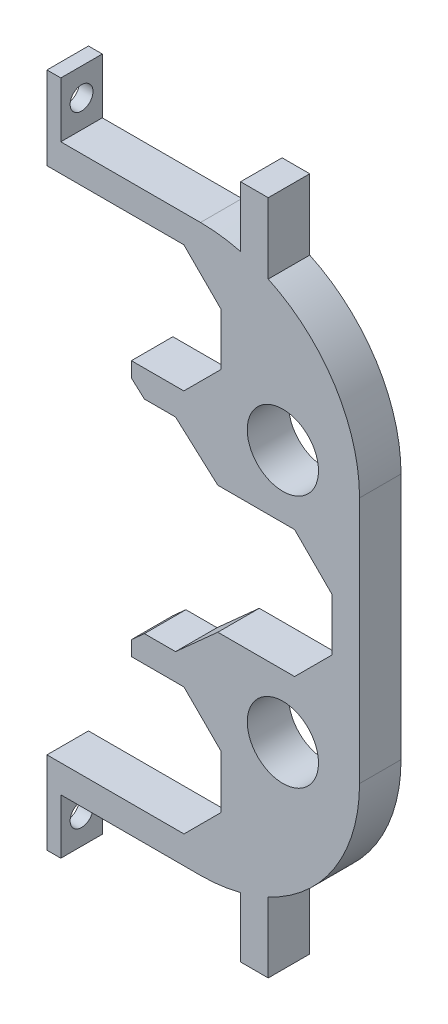
SolidWorks part; units mm, degrees
ref_plane "前视基准面" through (0, 0, 0) normal (0, 0, 1) x (1, 0, 0)
ref_plane "上视基准面" through (0, 0, 0) normal (0, 1, 0) x (1, 0, 0)
ref_plane "右视基准面" through (0, 0, 0) normal (1, 0, 0) x (0, 0, -1)
other "Configuration Table"
sketch "草图1" plane through (0, 0, 228) normal (0, 0, 1) x (1, 0, 0)
  line L0 (25.0533, -31.4628) -> (19.75, -36.7661) construction
  line L1 (19.75, -36.7661) -> (12.25, -36.7661) construction
  line L2 (12.25, -36.7661) -> (6.9467, -31.4628) construction
  line L3 (6.9467, -31.4628) -> (6.9467, -23.9628) construction
  line L4 (6.9467, -23.9628) -> (12.25, -18.6595) construction
  line L5 (12.25, -18.6595) -> (19.75, -18.6595) construction
  line L6 (19.75, -18.6595) -> (25.0533, -23.9628) construction
  line L7 (25.0533, -23.9628) -> (25.0533, -31.4628) construction
  line L8 (41.0533, -3.75) -> (35.75, -9.0533) construction
  line L9 (35.75, -9.0533) -> (28.25, -9.0533) construction
  line L10 (28.25, -9.0533) -> (22.9467, -3.75) construction
  line L11 (22.9467, -3.75) -> (22.9467, 3.75) construction
  line L12 (22.9467, 3.75) -> (28.25, 9.0533) construction
  line L13 (28.25, 9.0533) -> (35.75, 9.0533) construction
  line L14 (35.75, 9.0533) -> (41.0533, 3.75) construction
  line L15 (41.0533, 3.75) -> (41.0533, -3.75) construction
  line L16 (25.0533, 23.9628) -> (19.75, 18.6595) construction
  line L17 (19.75, 18.6595) -> (12.25, 18.6595) construction
  line L18 (12.25, 18.6595) -> (6.9467, 23.9628) construction
  line L19 (6.9467, 23.9628) -> (6.9467, 31.4628) construction
  line L20 (6.9467, 31.4628) -> (12.25, 36.7661) construction
  line L21 (12.25, 36.7661) -> (19.75, 36.7661) construction
  line L22 (19.75, 36.7661) -> (25.0533, 31.4628) construction
  line L23 (25.0533, 31.4628) -> (25.0533, 23.9628) construction
  line L24 (25.0533, -31.4628) -> (19.75, -36.7661) construction
  line L25 (19.75, -36.7661) -> (12.25, -36.7661) construction
  line L26 (12.25, -36.7661) -> (6.9467, -31.4628) construction
  line L27 (6.9467, -31.4628) -> (6.9467, -23.9628) construction
  line L28 (6.9467, -23.9628) -> (12.25, -18.6595) construction
  line L29 (12.25, -18.6595) -> (19.75, -18.6595) construction
  line L30 (19.75, -18.6595) -> (25.0533, -23.9628) construction
  line L31 (25.0533, -23.9628) -> (25.0533, -31.4628) construction
  line L32 (41.0533, -3.75) -> (35.75, -9.0533) construction
  line L33 (35.75, -9.0533) -> (28.25, -9.0533) construction
  line L34 (28.25, -9.0533) -> (22.9467, -3.75) construction
  line L35 (22.9467, -3.75) -> (22.9467, 3.75) construction
  line L36 (22.9467, 3.75) -> (28.25, 9.0533) construction
  line L37 (28.25, 9.0533) -> (35.75, 9.0533) construction
  line L38 (35.75, 9.0533) -> (41.0533, 3.75) construction
  line L39 (41.0533, 3.75) -> (41.0533, -3.75) construction
  line L40 (25.0533, 23.9628) -> (19.75, 18.6595) construction
  line L41 (19.75, 18.6595) -> (12.25, 18.6595) construction
  line L42 (12.25, 18.6595) -> (6.9467, 23.9628) construction
  line L43 (6.9467, 23.9628) -> (6.9467, 31.4628) construction
  line L44 (6.9467, 31.4628) -> (12.25, 36.7661) construction
  line L45 (12.25, 36.7661) -> (19.75, 36.7661) construction
  line L46 (19.75, 36.7661) -> (25.0533, 31.4628) construction
  line L47 (25.0533, 31.4628) -> (25.0533, 23.9628) construction
  line L48 (25.1533, 23.9214) -> (19.7914, 18.5595)
  line L49 (19.7914, 18.5595) -> (12.2086, 18.5595)
  line L53 (12.2086, 36.8661) -> (19.7914, 36.8661)
  line L54 (19.7914, 36.8661) -> (25.1533, 31.5042)
  line L55 (25.1533, 31.5042) -> (25.1533, 23.9214)
  line L56 (41.2033, -3.8121) -> (35.8121, -9.2033)
  line L57 (35.8121, -9.2033) -> (28.1879, -9.2033)
  line L61 (28.1879, 9.2033) -> (35.8121, 9.2033)
  line L62 (35.8121, 9.2033) -> (41.2033, 3.8121)
  line L63 (41.2033, 3.8121) -> (41.2033, -3.8121)
  line L64 (25.2033, -31.5249) -> (19.8121, -36.9161)
  line L65 (19.8121, -36.9161) -> (12.1879, -36.9161)
  line L69 (12.1879, -18.5095) -> (19.8121, -18.5095)
  line L70 (19.8121, -18.5095) -> (25.2033, -23.9007)
  line L71 (25.2033, -23.9007) -> (25.2033, -31.5249)
  line L72 (12.2086, 36.8661) -> (0, 36.8661)
  line L73 (0, 40.8661) -> (22.2033, 40.8661)
  line L74 (0, 40.8661) -> (0, 36.8661)
  line L75 (0, -40.9161) -> (22.2033, -40.9161)
  line L76 (45.2033, 17.8661) -> (45.2033, -17.9161)
  line L77 (12.2086, 18.5595) -> (12.2086, 16.3804)
  line L78 (6.8467, 31.5042) -> (12.2086, 36.8661) construction
  line L79 (6.8467, 23.9214) -> (6.8467, 31.5042) construction
  line L80 (12.2086, 18.5595) -> (6.8467, 23.9214) construction
  line L81 (24.7066, 9.2033) -> (28.1879, 9.2033)
  line L82 (22.7967, -3.8121) -> (22.7967, 3.8121) construction
  line L83 (22.7967, 3.8121) -> (28.1879, 9.2033) construction
  line L84 (28.1879, -9.2033) -> (22.7967, -3.8121) construction
  line L85 (28.1879, -9.2033) -> (24.7066, -9.2033)
  line L87 (12.1879, -36.9161) -> (0, -36.9161)
  line L88 (6.7967, -23.9007) -> (12.1879, -18.5095) construction
  line L89 (6.7967, -31.5249) -> (6.7967, -23.9007) construction
  line L90 (12.1879, -36.9161) -> (6.7967, -31.5249) construction
  line L91 (0, -36.9161) -> (0, -40.9161)
  line L92 (0, 51.3093) -> (0, -58.2946) construction
  line L93 (12.2086, 16.3804) -> (14.0899, 14.6919)
  line L94 (14.0899, 14.6919) -> (18.5913, 14.6919)
  line L95 (18.5913, 14.6919) -> (24.7066, 9.2033)
  line L97 (0, 0) -> (54.2618, 0) construction
  line L102 (12.1879, -18.5095) -> (12.2086, -16.3804)
  line L103 (18.5913, -14.6919) -> (24.7066, -9.2033)
  line L104 (14.0899, -14.6919) -> (18.5913, -14.6919)
  line L105 (12.2086, -16.3804) -> (14.0899, -14.6919)
  line L106 (0, 0) -> (57.7065, -33.3168) construction
  arc A0 (22.2033, -40.9161) -> (45.2033, -17.9161) centre (22.2033, -17.9161) ccw
  arc A1 (22.2033, 40.8661) -> (45.2033, 17.8661) centre (22.2033, 17.8661) cw
  dimension "D7" = 23
  dimension "D4" = 4
  dimension "D5" = 4
  dimension "D6" = 4
  dimension "D8" = 30
  dimension "D1" = 0.1
  dimension "D2" = 0.15
  dimension "D3" = 0.15
extrude "凸台-拉伸1" add sketch "草图1" against normal blind 6
sketch "草图2" plane through (0, 0, 0) normal (-1, 0, 0) x (0, 0, 1)
  line L0 (228, 40.8661) -> (222, 48.8661) construction
  line L1 (228, 40.8661) -> (222, 40.8661)
  line L2 (228, 40.8661) -> (228, 48.8661)
  line L3 (228, 48.8661) -> (222, 48.8661)
  line L4 (222, 40.8661) -> (222, 48.8661)
  line L5 (228, 48.8661) -> (222, 40.8661) construction
  line L6 (0, 0) -> (13.1408, 0) construction
  line L7 (228, -48.8661) -> (222, -48.8661)
  line L8 (222, -40.8661) -> (222, -48.8661)
  line L9 (228, -40.8661) -> (222, -40.8661)
  line L10 (228, -40.8661) -> (228, -48.8661)
  circle A0 centre (225, 44.8661) radius 1.65
  circle A1 centre (225, -44.8661) radius 1.65
  dimension "D1" = 3.3
  dimension "D2" = 8
extrude "凸台-拉伸2" add sketch "草图2" against normal blind 2
sketch "草图3" plane through (0, 0, 0) normal (-1, 0, 0) x (0, 0, 1)
  line L0 (0, 0) -> (10.4173, 0) construction
  line L1 (228, 36.8661) -> (222, 36.8661)
  line L2 (228, 36.8661) -> (228, 48.8661)
  line L3 (228, 48.8661) -> (222, 48.8661)
  line L4 (222, 36.8661) -> (222, 48.8661)
  line L5 (228, -48.8661) -> (222, -48.8661)
  line L6 (222, -36.8661) -> (222, -48.8661)
  line L7 (228, -36.8661) -> (222, -36.8661)
  line L8 (228, -36.8661) -> (228, -48.8661)
extrude "凸台-拉伸3" add sketch "草图3" along normal blind 4 from offset 32 offset against normal yes
sketch "草图4" plane through (0, 0, 222) normal (0, 0, -1) x (-1, 0, 0)
  line L0 (0, 0) -> (-56.3889, 0) construction
  circle A6 centre (-34.1164, 18.2922) radius 5.15
  circle A7 centre (-34.1164, -18.2922) radius 5.15
  dimension "D1" = 10.3
extrude "切除-拉伸1" cut sketch "草图4" against normal up to next
